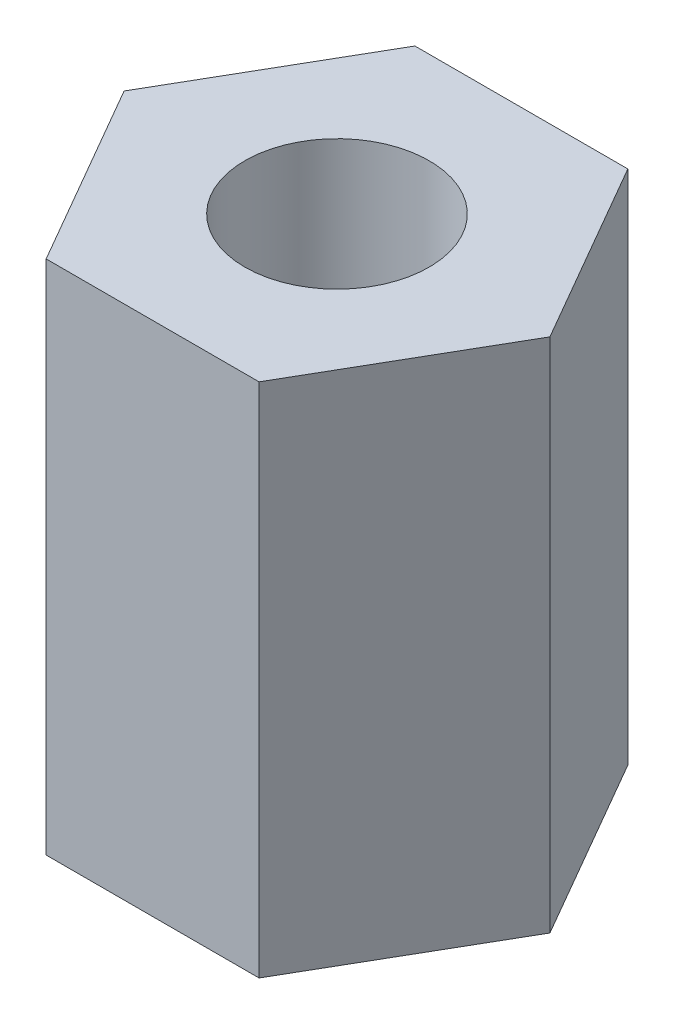
SolidWorks part; units mm, degrees
ref_plane "前视基准面" through (0, 0, 0) normal (0, 0, 1) x (1, 0, 0)
ref_plane "上视基准面" through (0, 0, 0) normal (0, 1, 0) x (1, 0, 0)
ref_plane "右视基准面" through (0, 0, 0) normal (1, 0, 0) x (0, 0, -1)
ref_plane "基准面4" through (0, 0, 0) normal (0, -1, 0) x (1, 0, 0)
sketch "草图1" plane through (0, 0, 0) normal (0, -1, 0) x (1, 0, 0)
  line L0 (-1.4434, -2.5) -> (1.4434, -2.5)
  line L1 (1.4434, -2.5) -> (2.8868, 0)
  line L2 (2.8868, 0) -> (1.4434, 2.5)
  line L3 (1.4434, 2.5) -> (-1.4434, 2.5)
  line L4 (-1.4434, 2.5) -> (-2.8868, 0)
  line L5 (-2.8868, 0) -> (-1.4434, -2.5)
  circle A0 centre (0, 0) radius 1.25
extrude "凸台-拉伸1" add sketch "草图1" against normal blind 7
